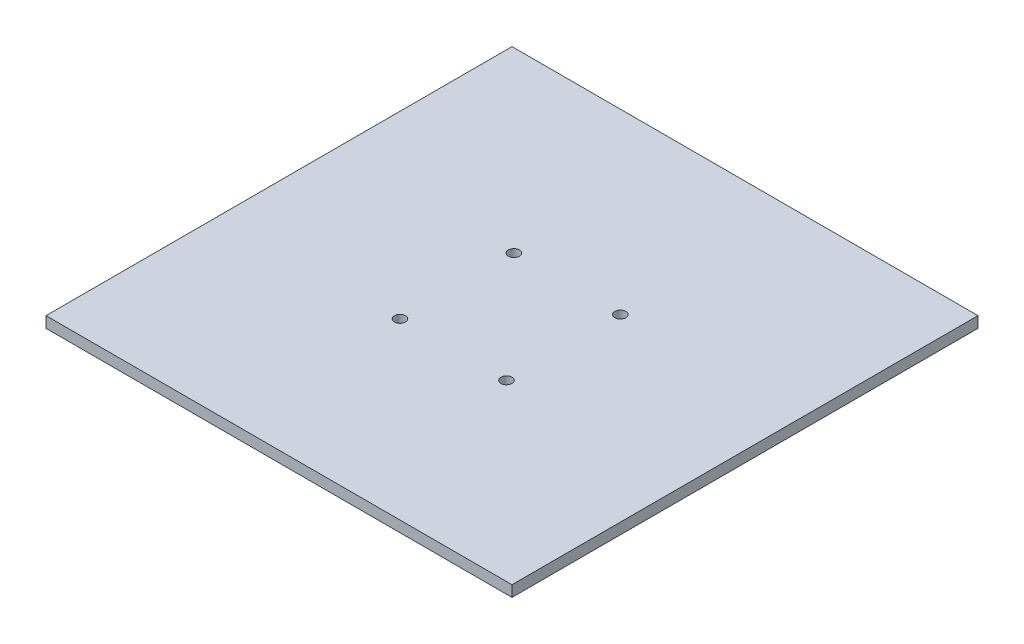
SolidWorks part; units mm, degrees
ref_plane "Front Plane" through (0, 0, 0) normal (0, 0, 1) x (1, 0, 0)
ref_plane "Top Plane" through (0, 0, 0) normal (0, 1, 0) x (1, 0, 0)
ref_plane "Right Plane" through (0, 0, 0) normal (1, 0, 0) x (0, 0, -1)
sketch "Sketch2" plane through (0, 0, 0) normal (0, 1, 0) x (1, 0, 0)
  line L1 (63.4385, 63.4385) -> (63.4385, -63.4385)
  line L2 (63.4385, -63.4385) -> (-63.4385, -63.4385)
  line L3 (-63.4385, -63.4385) -> (-63.4385, 63.4385)
  line L4 (-63.4385, 63.4385) -> (63.4385, 63.4385)
  circle A0 centre (14.5, 15) radius 1.5
  circle A1 centre (-14.5, 15) radius 1.5
  circle A2 centre (-14.5, -16) radius 1.5
  circle A3 centre (14.5, -16) radius 1.5
extrude "Boss-Extrude1" add sketch "Sketch2" along normal blind 3
